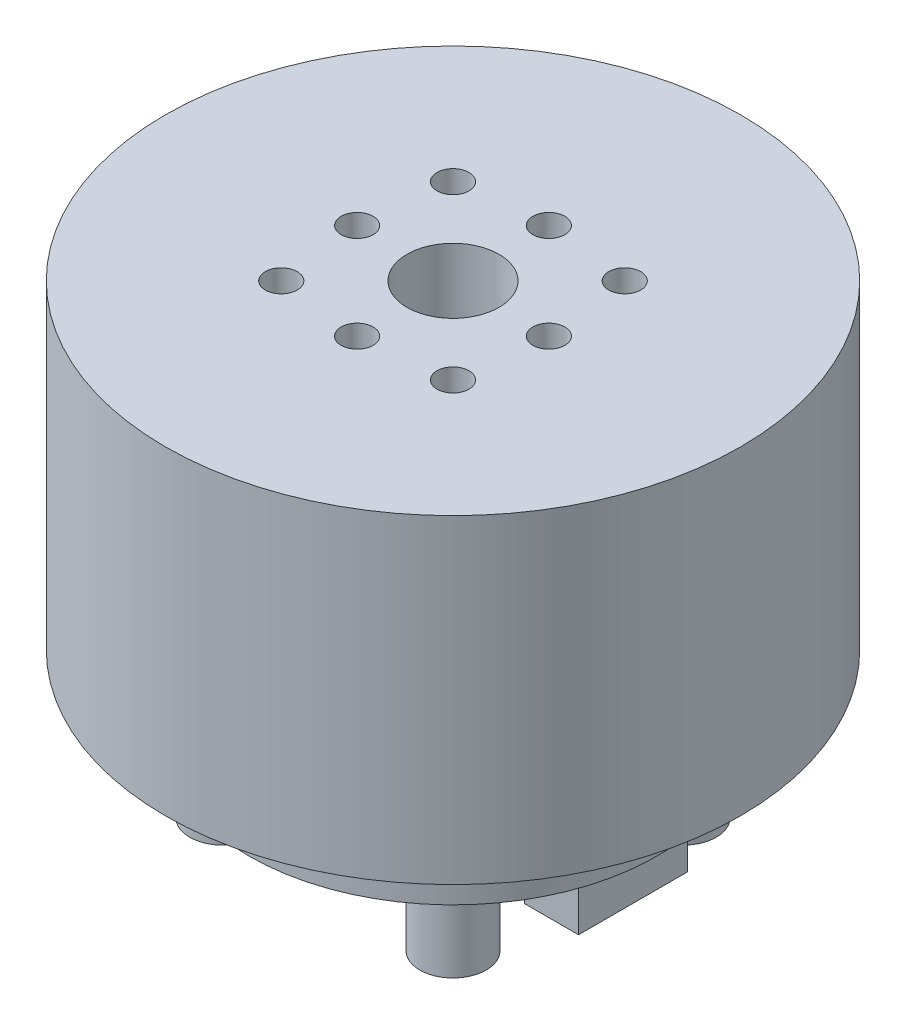
SolidWorks part; units mm, degrees
material "BUTYL"
ref_plane "前视基准面" through (0, 0, 0) normal (0, 0, 1) x (1, 0, 0)
ref_plane "上视基准面" through (0, 0, 0) normal (0, 1, 0) x (1, 0, 0)
ref_plane "右视基准面" through (0, 0, 0) normal (1, 0, 0) x (0, 0, -1)
other "Configuration Table"
sketch "草图1" plane through (0, 0, 0) normal (0, 1, 0) x (1, 0, 0)
  circle A0 centre (0, 0) radius 22.5
  dimension "D1" = 45
extrude "凸台-拉伸1" add sketch "草图1" along normal blind 25
sketch "草图2" plane through (0, 0, 0) normal (0, -1, 0) x (1, 0, 0)
  circle A0 centre (0, 0) radius 15.96
  circle A1 centre (0, 0) radius 22.5
  circle A2 centre (0, 0) radius 22.5
  dimension "D2" = 31.92
  dimension "D1" = 0
extrude "凸台-拉伸2" add sketch "草图2" along normal blind 6 contours A0
sketch "草图3" plane through (0, -6, 0) normal (0, -1, 0) x (1, 0, 0)
  line L1 (-9, -9) -> (9, -9)
  line L2 (-9, -9) -> (-9, 9)
  line L3 (-9, 9) -> (9, 9)
  line L4 (9, -9) -> (9, 9)
  line L5 (-9, -9) -> (9, 9) construction
  line L6 (-9, 9) -> (9, -9) construction
  circle A0 centre (-9, 9) radius 1.4
  circle A1 centre (0, 0) radius 15.96
  circle A2 centre (0, 0) radius 15.96
  circle A3 centre (9, 9) radius 1.4
  circle A4 centre (-9, -9) radius 1.4
  circle A5 centre (9, -9) radius 1.4
  circle A6 centre (-9, 9) radius 2.6
  circle A7 centre (9, 9) radius 2.6
  circle A8 centre (-9, -9) radius 2.6
  circle A9 centre (9, -9) radius 2.6
  dimension "D4" = 2.8
  dimension "D5" = 2.8
  dimension "D6" = 2.8
  dimension "D7" = 2.8
  dimension "D2" = 18
  dimension "D3" = 18
  dimension "D1" = 0
  dimension "D8" = 1.2
  dimension "D9" = 1.2
extrude "凸台-拉伸3" add sketch "草图3" along normal blind 5.4 contours L3 A6 L2 A0 | L2 A6 L3 A0 | L4 A7 L3 A3 | L3 A7 L4 A3 | L1 A9 L4 A5 | L4 A9 L1 A5 | L1 A8 L2 A4 | L2 A8 L1 A4
sketch "草图4" plane through (0, -6, 0) normal (0, -1, 0) x (1, 0, 0)
  line L0 (0, 0) -> (15.96, 0)
  line L1 (14.09, 0) -> (15.96, 0)
  line L2 (9.88, -4.27) -> (14.09, -4.27)
  line L3 (9.88, -4.27) -> (9.88, 4.27)
  line L4 (9.88, 4.27) -> (14.09, 4.27)
  line L5 (14.09, -4.27) -> (14.09, 4.27)
  line L6 (9.88, -4.27) -> (14.09, 4.27) construction
  line L7 (9.88, 4.27) -> (14.09, -4.27) construction
  line L8 (0, 0) -> (0, 6.1767)
  line L9 (-9.88, 4.27) -> (-14.09, 4.27)
  line L10 (-14.09, -4.27) -> (-14.09, 4.27)
  line L11 (-9.88, -4.27) -> (-14.09, -4.27)
  line L12 (-9.88, -4.27) -> (-9.88, 4.27)
  circle A1 centre (0, 0) radius 15.96
  circle A2 centre (0, 0) radius 15.96
  point P0 (11.985, 0)
  dimension "D2" = 4.21
  dimension "D3" = 8.54
  dimension "D4" = 1.87
  dimension "D1" = 0
extrude "凸台-拉伸4" add sketch "草图4" along normal blind 4.13 contours L11 L12 L9 L10 | L2 L5 L0 L3 | L0 L5 L4 L3
sketch "草图5" plane through (0, 25, 0) normal (0, 1, 0) x (1, 0, 0)
  line L0 (0, 0) -> (22.5, 0)
  line L2 (0, 22.5) -> (0, 0)
  line L3 (0, 0) -> (15.9099, 15.9099)
  line L4 (0, 0) -> (15.9099, -15.9099)
  circle A0 centre (0, 0) radius 7.5
  circle A1 centre (0, 0) radius 22.5
  circle A2 centre (0, 0) radius 22.5
  circle A3 centre (7.5, 0) radius 1.25
  circle A4 centre (-7.5, 0) radius 1.25
  circle A5 centre (0, 7.5) radius 1.25
  circle A6 centre (0, -7.5) radius 1.25
  circle A7 centre (0, 0) radius 9.5
  circle A8 centre (6.7175, 6.7175) radius 1.25
  circle A9 centre (-6.7175, -6.7175) radius 1.25
  circle A10 centre (6.7175, -6.7175) radius 1.25
  circle A11 centre (-6.7175, 6.7175) radius 1.25
  dimension "D2" = 15
  dimension "D3" = 2.5
  dimension "D4" = 2.5
  dimension "D5" = 19
  dimension "D6" = 2.5
  dimension "D7" = 2.5
  dimension "D1" = 0
extrude "切除-拉伸1" cut sketch "草图5" against normal blind 3 contours L4 A10 A7 | A7 A10 L4 | L4 A10 A7 | A7 A10 L4 | A0 A3 L0 | L0 A3 A0 | A0 A3 L0 | L0 A3 A0 | A7 A8 L3 | L3 A8 A7 | A7 A8 L3 | L3 A8 A7 | A0 A5 L2 | L2 A5 A0 | A0 A5 L2 | L2 A5 A0 | A11 A7 | A11 A7 | A4 A0 | A4 A0 | A9 A7 | A9 A7 | A6 A0 | A6 A0
sketch "草图6" plane through (0, 25, 0) normal (0, 1, 0) x (1, 0, 0)
  circle A0 centre (0, 0) radius 3.6
  circle A1 centre (0, 0) radius 22.5
  circle A2 centre (0, 0) radius 22.5
  dimension "D2" = 7.2
  dimension "D1" = 0
extrude "切除-拉伸2" cut sketch "草图6" against normal up to surface (25 mm away) contours A0 up to face at (0, 0, -15.96)
